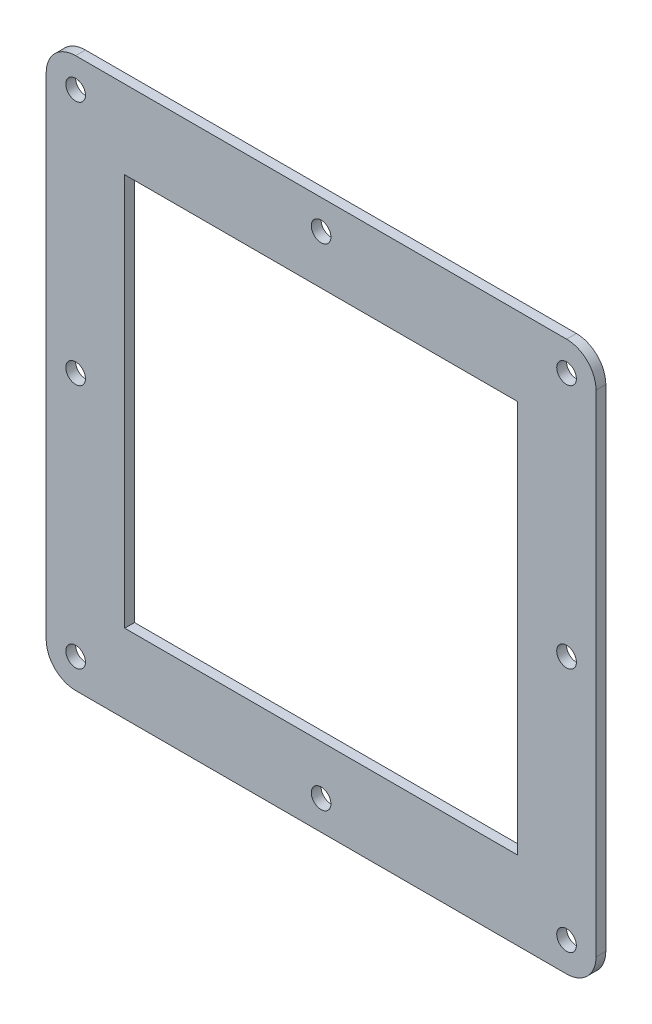
SolidWorks part; units mm, degrees
ref_plane "Front Plane" through (0, 0, 0) normal (0, 0, 1) x (1, 0, 0)
ref_plane "Top Plane" through (0, 0, 0) normal (0, 1, 0) x (1, 0, 0)
ref_plane "Right Plane" through (0, 0, 0) normal (1, 0, 0) x (0, 0, -1)
sketch "Sketch2" plane through (0, 0, 0) normal (0, 0, 1) x (1, 0, 0)
  line L0 (-125, 125) -> (125, 125) construction
  line L1 (-125, 140) -> (125, 140)
  line L2 (-140, 125) -> (-140, -125)
  line L3 (-125, -140) -> (125, -140)
  line L4 (140, 125) -> (140, -125)
  line L5 (-140, 140) -> (140, -140) construction
  line L6 (-140, -140) -> (140, 140) construction
  line L7 (125, 125) -> (125, -125) construction
  line L8 (125, -125) -> (-125, -125) construction
  line L9 (-125, -125) -> (-125, 125) construction
  arc A0 (-140, -125) -> (-125, -140) centre (-125, -125) ccw
  arc A1 (125, -140) -> (140, -125) centre (125, -125) ccw
  arc A2 (125, 140) -> (140, 125) centre (125, 125) cw
  arc A3 (-125, 140) -> (-140, 125) centre (-125, 125) ccw
  circle A4 centre (-125, 125) radius 5
  circle A5 centre (0, 125) radius 5
  circle A6 centre (125, 125) radius 5
  circle A13 centre (0, 0) radius 4
  circle A14 centre (125, 0) radius 5
  circle A15 centre (-125, 0) radius 5
  circle A16 centre (-125, -125) radius 5
  circle A17 centre (0, -125) radius 5
  circle A18 centre (125, -125) radius 5
  point P0 (0, 0)
  dimension "D3" = 15
  dimension "D4" = 10
  dimension "D5" = 10
  dimension "D6" = 10
  dimension "D7" = 8
  dimension "D8" = 10
  dimension "D9" = 10
  dimension "D10" = 10
  dimension "D11" = 10
  dimension "D1" = 280
  dimension "D2" = 280
extrude "Boss-Extrude1" add sketch "Sketch2" along normal blind 5
sketch "Sketch3" plane through (0, 0, 5) normal (0, 0, 1) x (1, 0, 0)
  line L1 (-100, 100) -> (100, 100)
  line L2 (-100, 100) -> (-100, -100)
  line L3 (-100, -100) -> (100, -100)
  line L4 (100, 100) -> (100, -100)
  line L5 (-100, 100) -> (100, -100) construction
  line L6 (-100, -100) -> (100, 100) construction
  point P0 (0, 0)
  dimension "D1" = 200
  dimension "D2" = 200
extrude "Cut-Extrude1" cut sketch "Sketch3" against normal blind 10
